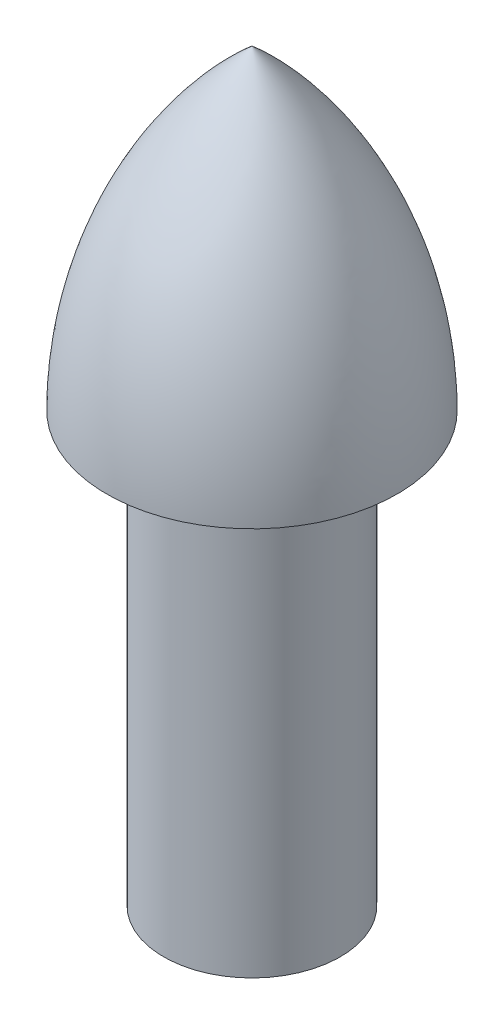
SolidWorks part; units mm, degrees
ref_plane "前视基准面" through (0, 0, 0) normal (0, 0, 1) x (1, 0, 0)
ref_plane "上视基准面" through (0, 0, 0) normal (0, 1, 0) x (1, 0, 0)
ref_plane "右视基准面" through (0, 0, 0) normal (1, 0, 0) x (0, 0, -1)
sketch "草图1" plane through (0, 0, 0) normal (0, 0, 1) x (1, 0, 0)
  line L0 (0, 0) -> (0, 1)
  line L1 (0, 6.25) -> (4.5, 6.25) construction
  line L2 (0, 1) -> (4.7131, 1)
  line L3 (0, 0) -> (5.75, 0)
  line L4 (0, 11.1446) -> (0, 12.5)
  line L5 (0, 1) -> (5.75, 1) construction
  arc A0 (5.75, 0) -> (0, 12.5) centre (-10.875, -0.075) ccw
  arc A1 (4.7131, 1) -> (0, 11.1446) centre (-10.875, -0.075) ccw
  arc A3 (4.75, -0.0045) -> (-0.6541, 11.7436) centre (-10.875, -0.075) ccw construction
  dimension "D1" = 12.5
  dimension "D2" = 5.75
  dimension "D3" = 4.5
  dimension "D6" = 6.25
  dimension "D4" = 1
  dimension "D5" = 1
revolve "旋转1" add sketch "草图1" angle 360 about L4
sketch "草图2" plane through (0, 0, 0) normal (0, -1, 0) x (1, 0, 0)
  circle A0 centre (0, 0) radius 3.5
  dimension "D2" = 7
extrude "凸台-拉伸1" add sketch "草图2" along normal blind 17
sketch "草图3" plane through (0, -17, 0) normal (0, -1, 0) x (1, 0, 0)
  circle A0 centre (0, 0) radius 2.25
  dimension "D1" = 4.5
extrude "切除-拉伸1" cut sketch "草图3" against normal blind 18
